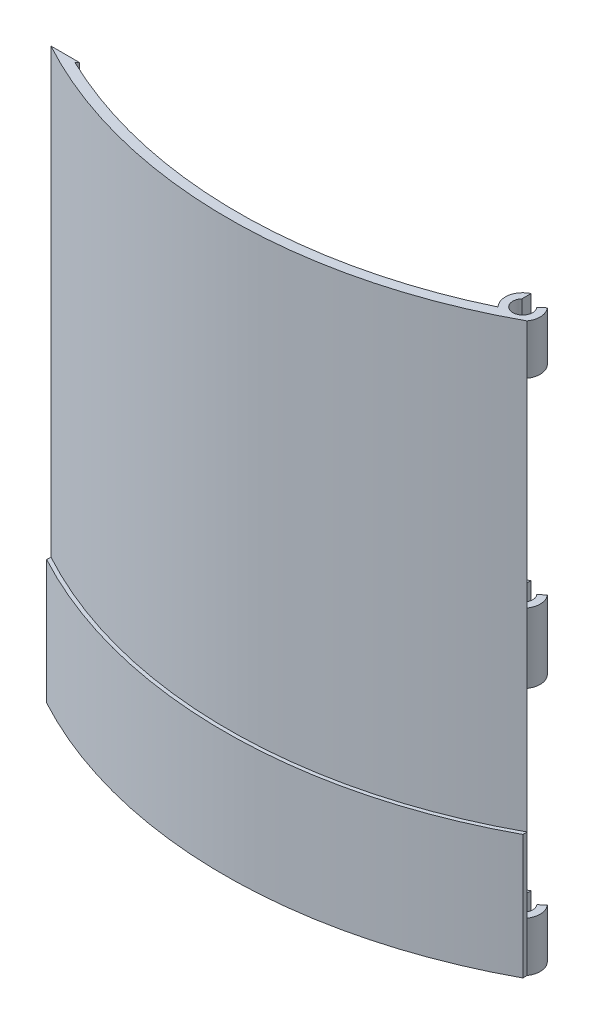
SolidWorks part; units mm, degrees
ref_plane "前视基准面" through (0, 0, 0) normal (0, 0, 1) x (1, 0, 0)
ref_plane "上视基准面" through (0, 0, 0) normal (0, 1, 0) x (1, 0, 0)
ref_plane "右视基准面" through (0, 0, 0) normal (1, 0, 0) x (0, 0, -1)
sketch "草图1" plane through (0, 0, 0) normal (0, 1, 0) x (1, 0, 0)
  line L0 (0, 0) -> (94, 0) construction
  line L1 (47, 0) -> (47, 58.1905) construction
  line L4 (92, 0) -> (92, 8.8253) construction
  line L5 (90.5, 3.3229) -> (90.5, 5.1623)
  line L7 (2, 0) -> (2, 8.8253) construction
  line L8 (0.5, 3.3229) -> (0.5, 5.1623)
  line L9 (3.5, 3.3229) -> (3.5, 5.1623)
  line L10 (93.5, 3.3229) -> (94.625, 4.315)
  arc A0 (-0.8723, 0) -> (94.8723, 0) centre (47, 87.7966) ccw
  arc A1 (4.4604, -0.4892) -> (89.5396, -0.4892) centre (47, 87.7966) ccw
  arc A2 (94.8723, 0) -> (94.625, 4.315) centre (92, 2) ccw
  arc A3 (90.5, 3.3229) -> (93.5, 3.3229) centre (92, 2) ccw
  arc A4 (90.5, 5.1623) -> (89.5396, -0.4892) centre (92, 2) ccw
  arc A5 (-0.8723, 0) -> (0.5, 5.1623) centre (2, 2) cw
  arc A6 (3.5, 5.1623) -> (4.4604, -0.4892) centre (2, 2) cw
  arc A7 (3.5, 3.3229) -> (0.5, 3.3229) centre (2, 2) cw
  dimension "D2" = 200
  dimension "D3" = 196
  dimension "D4" = 1.5
  dimension "D5" = 4
  dimension "D1" = 94
  dimension "D6" = 2
  dimension "D7" = 2
  dimension "D8" = 3
extrude "凸台-拉伸1" add sketch "草图1" along normal blind 114
sketch "草图3" plane through (0, 0, 0) normal (0, -1, 0) x (1, 0, 0)
  line L0 (47, 12.2034) -> (47, -39.7184) construction
  line L1 (-0.8723, 0) -> (-0.8723, 0.8533)
  line L2 (94.8723, 0) -> (94.8723, 0.8533)
  arc A0 (94.8723, 0) -> (-0.8723, 0) centre (47, -87.7966) ccw construction
  arc A1 (94.8723, 0) -> (-0.8723, 0) centre (47, -87.7966) ccw
  arc A2 (94.8723, 0.8533) -> (-0.8723, 0.8533) centre (47, -87.7966) ccw
  dimension "D2" = 201.5
extrude "凸台-拉伸2" add sketch "草图3" against normal blind 25
sketch "草图4" plane through (0, 0, 0) normal (0, 0, 1) x (1, 0, 0)
  line L0 (4.4604, 0) -> (89.5396, 0) construction
  line L1 (100.7687, 104) -> (84.5309, 104)
  line L2 (100.7687, 104) -> (100.7687, 64)
  line L3 (100.7687, 10) -> (84.5309, 10)
  line L4 (84.5309, 104) -> (84.5309, 64)
  line L5 (-8.4538, 64) -> (10.3883, 64)
  line L6 (-8.4538, 64) -> (-8.4538, 114)
  line L7 (-8.4538, 114) -> (10.3883, 114)
  line L8 (10.3883, 64) -> (10.3883, 114)
  line L9 (-8.4538, 0) -> (11.4606, 0)
  line L10 (-8.4538, 0) -> (-8.4538, 50)
  line L11 (-8.4538, 50) -> (11.4606, 50)
  line L12 (11.4606, 0) -> (11.4606, 50)
  line L13 (89.5396, 114) -> (4.4604, 114) construction
  line L14 (90, 0) -> (94, 0) construction
  line L15 (100.7687, 64) -> (84.5309, 64)
  line L16 (84.5309, 50) -> (100.7687, 50)
  line L17 (100.7687, 50) -> (100.7687, 10)
  line L18 (84.5309, 50) -> (84.5309, 10)
  dimension "D1" = 50
  dimension "D2" = 50
  dimension "D3" = 10
  dimension "D4" = 10
extrude "切除-拉伸1" cut sketch "草图4" against normal blind 20
